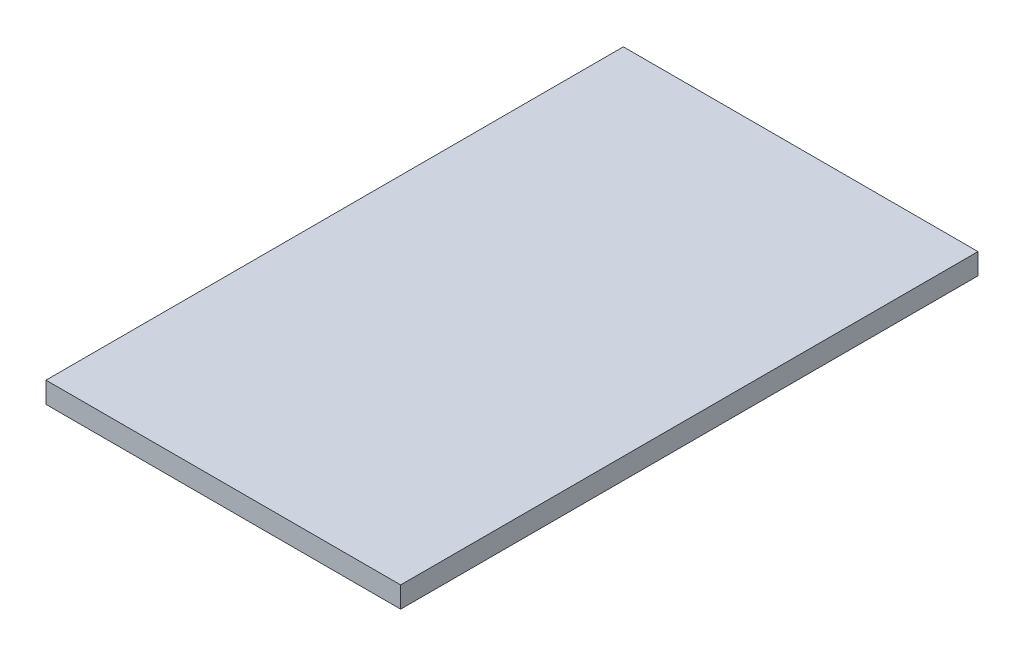
SolidWorks part; units mm, degrees
ref_plane "前视基准面" through (0, 0, 0) normal (0, 0, 1) x (1, 0, 0)
ref_plane "上视基准面" through (0, 0, 0) normal (0, 1, 0) x (1, 0, 0)
ref_plane "右视基准面" through (0, 0, 0) normal (1, 0, 0) x (0, 0, -1)
other "Configuration Table"
sketch "草图1" plane through (0, 0, 0) normal (0, 1, 0) x (1, 0, 0)
  line L1 (-21.5, -35) -> (21.5, -35)
  line L2 (-21.5, -35) -> (-21.5, 35)
  line L3 (-21.5, 35) -> (21.5, 35)
  line L4 (21.5, -35) -> (21.5, 35)
  line L5 (-21.5, -35) -> (21.5, 35) construction
  line L6 (-21.5, 35) -> (21.5, -35) construction
  point P0 (0, 0)
  dimension "D1" = 43
  dimension "D2" = 70
extrude "凸台-拉伸1" add sketch "草图1" along normal blind 2.55
sketch "草图2" plane through (0, 0, 0) normal (0, -1, 0) x (-1, 0, 0)
  line L0 (-21.5, 35) -> (21.5, 35) construction
  line L1 (10.16, 32.46) -> (-10.16, 32.46)
  line L2 (10.16, 32.46) -> (10.16, 35)
  line L3 (10.16, 35) -> (-10.16, 35)
  line L4 (-10.16, 32.46) -> (-10.16, 35)
  line L5 (-21.5, 35) -> (21.5, 35) construction
  line L6 (0, 35) -> (0, 36.8901) construction
  point P9 (0, 0)
  dimension "D1" = 2.54
  dimension "D2" = 20.32
extrude "凸台-拉伸2" add sketch "草图2" along normal blind 2.5
